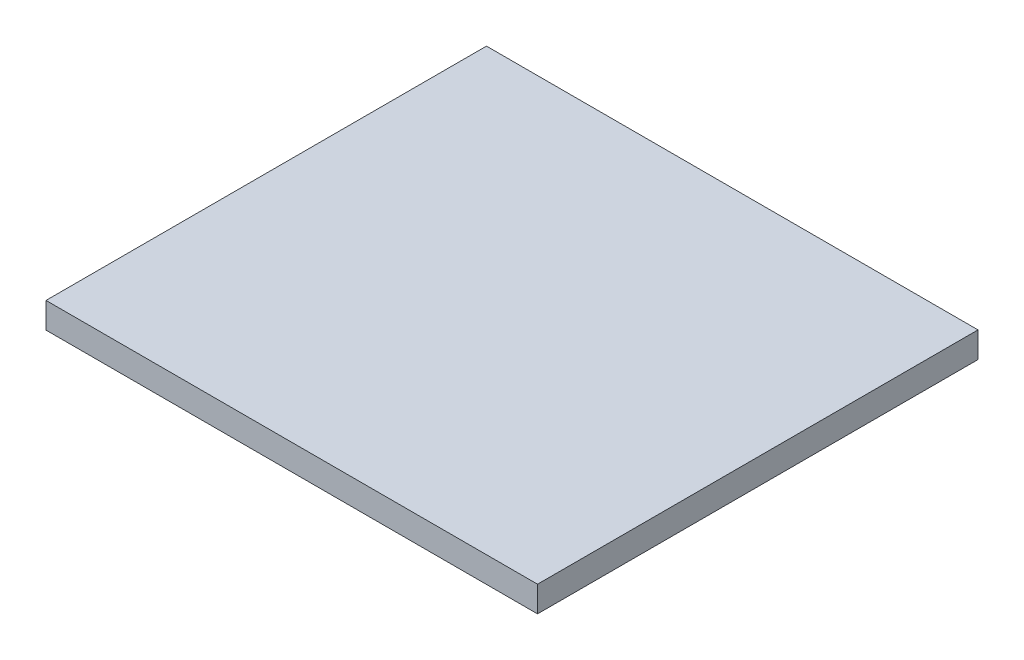
SolidWorks part; units mm, degrees
ref_plane "Front Plane" through (0, 0, 0) normal (0, 0, 1) x (1, 0, 0)
ref_plane "Top Plane" through (0, 0, 0) normal (0, 1, 0) x (1, 0, 0)
ref_plane "Right Plane" through (0, 0, 0) normal (1, 0, 0) x (0, 0, -1)
other "Configuration Table"
sketch "Sketch1" plane through (0, 0, 0) normal (0, 1, 0) x (1, 0, 0)
  line L1 (-91.8448, 80.0245) -> (99.1815, 80.0245)
  line L2 (-91.8448, 80.0245) -> (-91.8448, -91.1654)
  line L3 (-91.8448, -91.1654) -> (99.1815, -91.1654)
  line L4 (99.1815, 80.0245) -> (99.1815, -91.1654)
extrude "Boss-Extrude1" add sketch "Sketch1" along normal blind 10
sketch "Circles" plane through (0, 0, 0) normal (0, 1, 0) x (1, 0, 0)
  circle A0 centre (-73.2072, 101.814) radius 8.6183
  circle A1 centre (-28.0471, 101.814) radius 9.2822
  circle A2 centre (20.5603, 101.814) radius 9.3078
  circle A3 centre (66.0651, 101.814) radius 12.0657
sketch "Triangles" plane through (0, 0, 0) normal (0, 1, 0) x (1, 0, 0)
  line L1 (-74.6641, 152.6042) -> (-86.878, 172.8407)
  line L2 (-86.878, 172.8407) -> (-98.2964, 152.1449)
  line L3 (-98.2964, 152.1449) -> (-74.6641, 152.6042)
  line L4 (-27.4012, 140.0259) -> (-25.8343, 170.8702)
  line L5 (-25.8343, 170.8702) -> (-53.3297, 156.8051)
  line L6 (-53.3297, 156.8051) -> (-27.4012, 140.0259)
  line L7 (22.643, 137.4836) -> (23.8914, 167.0041)
  line L8 (23.8914, 167.0041) -> (-2.2983, 153.325)
  line L9 (-2.2983, 153.325) -> (22.643, 137.4836)
  line L10 (57.596, 137.4836) -> (88.9199, 148.9192)
  line L11 (88.9199, 148.9192) -> (63.3544, 170.3287)
  line L12 (63.3544, 170.3287) -> (57.596, 137.4836)
  circle A0 centre (-86.6129, 159.1966) radius 6.8233 construction
  circle A1 centre (-35.5217, 155.9004) radius 8.9155 construction
  circle A2 centre (14.7454, 152.6042) radius 8.5294 construction
  circle A3 centre (69.9568, 152.2438) radius 9.6262 construction
